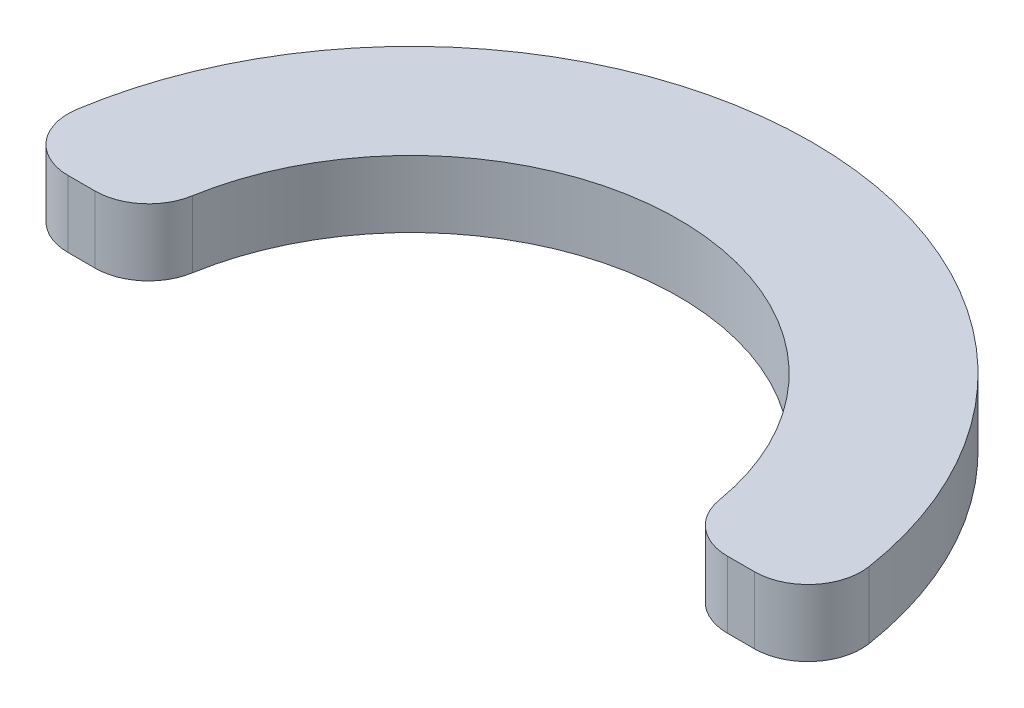
SolidWorks part; units mm, degrees
material "Custom Plastic"
ref_plane "X-Y Datum" through (0, 0, 0) normal (0, 0, 1) x (1, 0, 0)
ref_plane "X-Z Datum" through (0, 0, 0) normal (0, 1, 0) x (1, 0, 0)
ref_plane "Y-Z Datum" through (0, 0, 0) normal (1, 0, 0) x (0, 0, -1)
sketch "Sketch1" plane through (0, 0, 0) normal (0, 1, 0) x (1, 0, 0)
  line L0 (-12.7, 0) -> (-19.05, 0)
  line L1 (12.7, 0) -> (19.05, 0)
  arc A0 (12.7, 0) -> (-12.7, 0) centre (0, 0) ccw
  arc A1 (19.05, 0) -> (-19.05, 0) centre (0, 0) ccw
  point P6 (0, 12.7)
  dimension "D1" = 25.4
  dimension "D2" = 38.1
extrude "Boss-Extrude1" add sketch "Sketch1" along normal blind 3.175
fillet "Fillet1" radius 2.54 4 edges at (-19.05, 1.5875, 0) (-12.7, 1.5875, 0) (12.7, 1.5875, 0) (19.05, 1.5875, 0)
